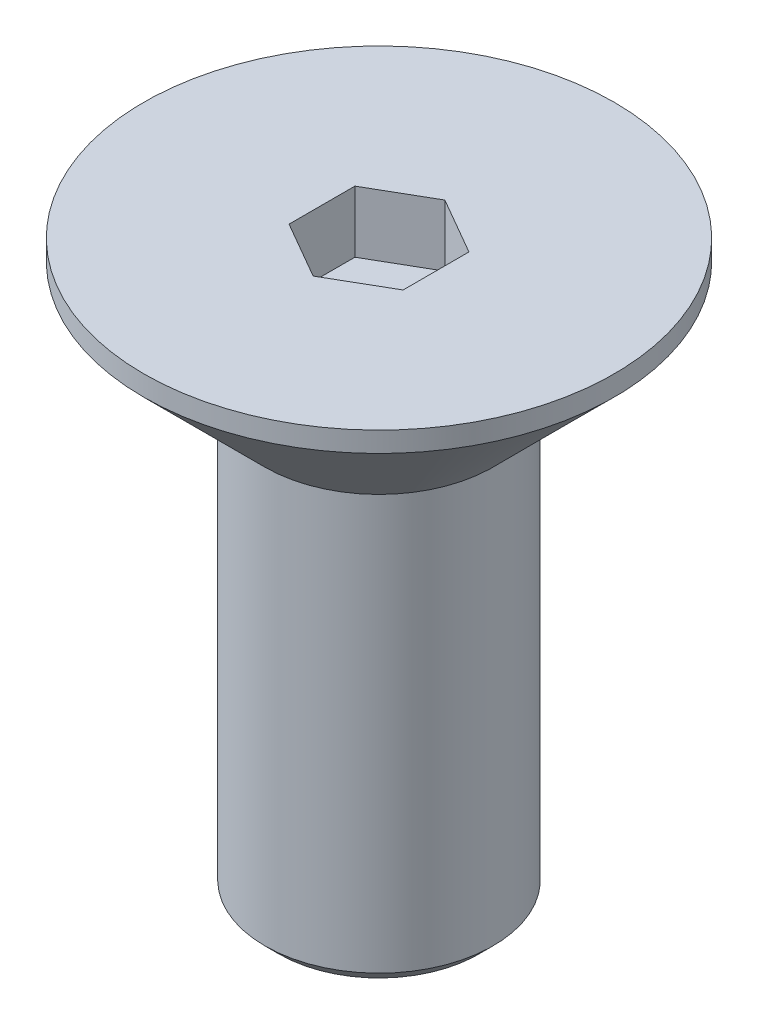
SolidWorks part; units mm, degrees
material "AISI 1015 Steel, Cold Drawn (SS)"
ref_plane "Front Plane" through (0, 0, 0) normal (0, 0, 1) x (1, 0, 0)
ref_plane "Top Plane" through (0, 0, 0) normal (0, 1, 0) x (1, 0, 0)
ref_plane "Right Plane" through (0, 0, 0) normal (1, 0, 0) x (0, 0, -1)
sketch "Sketch2" plane through (0, 0, 0) normal (0, 0, 1) x (1, 0, 0)
  line L0 (0, 0) -> (0, -25.1791) construction
  line L1 (0, 0) -> (8.25, 0)
  line L2 (8.25, 0) -> (8.25, -0.71)
  line L3 (8.25, -0.71) -> (4, -4.96)
  line L4 (4, -4.96) -> (4, -20)
  line L5 (4, -20) -> (0, -20)
  line L6 (0, -20) -> (0, 0)
  line L7 (8.25, -0.71) -> (0, -0.71) construction
  point P3 (0, 0)
  dimension "D1" = 20
  dimension "D2" = 16.5
  dimension "D3" = 8
  dimension "D4" = 4.96
  dimension "D5" = 45
revolve "Revolve1" add sketch "Sketch2" angle 360 about L0
cosmetic thread "Cosmetic Thread1" parameters "D2"=6.619
sketch "Sketch3" plane through (0, 0, 0) normal (0, 1, 0) x (1, 0, 0)
  line L0 (0, 2.3094) -> (2, 1.1547)
  line L1 (2, 1.1547) -> (2, -1.1547)
  line L2 (2, -1.1547) -> (0, -2.3094)
  line L3 (0, -2.3094) -> (-2, -1.1547)
  line L4 (-2, -1.1547) -> (-2, 1.1547)
  line L5 (-2, 1.1547) -> (0, 2.3094)
  circle A0 centre (0, 0) radius 2.3094 construction
  dimension "D1" = 4
extrude "Cut-Extrude1" cut sketch "Sketch3" against normal blind 2.16
chamfer "Chamfer1" distance 0.5 1 edges at (0, -20, 4)
